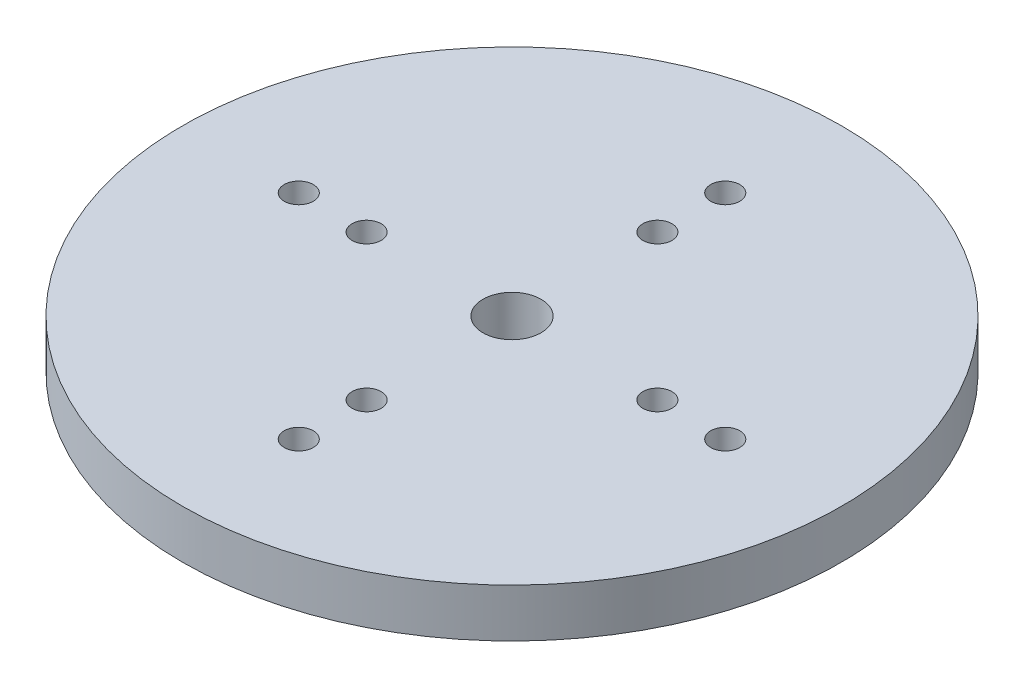
SolidWorks part; units mm, degrees
ref_plane "Front Plane" through (0, 0, 0) normal (0, 0, 1) x (1, 0, 0)
ref_plane "Top Plane" through (0, 0, 0) normal (0, 1, 0) x (1, 0, 0)
ref_plane "Right Plane" through (0, 0, 0) normal (1, 0, 0) x (0, 0, -1)
sketch "Sketch2" plane through (0, 0, 0) normal (0, 1, 0) x (1, 0, 0)
  circle A0 centre (0, 0) radius 34
  dimension "D1" = 68
extrude "Boss-Extrude1" add sketch "Sketch2" along normal blind 5
sketch "Sketch3" plane through (0, 0, 0) normal (0, -1, 0) x (1, 0, 0)
  circle A0 centre (0, 0) radius 22
  circle A1 centre (0, 22) radius 1.5
  circle A2 centre (0, 0) radius 22
  circle A3 centre (22, 0) radius 1.5
  circle A4 centre (0, 0) radius 22
  circle A5 centre (0, -22) radius 1.5
  circle A6 centre (0, 0) radius 22
  circle A7 centre (-22, 0) radius 1.5
  point P3 (0, 22)
  point P5 (22, 0)
  point P7 (0, -22)
  point P9 (-22, 0)
  point P29 (0, 0)
  dimension "D1" = 44
  dimension "D2" = 3
  dimension "D3" = 4
extrude "Cut-Extrude1" cut sketch "Sketch3" against normal blind 5 contours A1 | A7 | A5 | A3
sketch "Sketch5" plane through (0, 0, 0) normal (0, -1, 0) x (1, 0, 0)
  circle A0 centre (0, 0) radius 15
  circle A1 centre (0, 15) radius 1.5
  circle A2 centre (15, 0) radius 1.5
  circle A3 centre (0, -15) radius 1.5
  circle A4 centre (-15, 0) radius 1.5
  point P14 (0, 0)
  dimension "D1" = 30
  dimension "D2" = 3
  dimension "D3" = 4
extrude "Cut-Extrude2" cut sketch "Sketch5" against normal blind 5 contours A3 | A2 | A1 | A4
sketch "Sketch6" plane through (0, 0, 0) normal (0, -1, 0) x (1, 0, 0)
  circle A0 centre (0, 0) radius 10
  dimension "D1" = 20
extrude "Boss-Extrude2" add sketch "Sketch6" along normal blind 5
sketch "Sketch7" plane through (0, -5, 0) normal (0, -1, 0) x (-1, 0, 0)
  line L0 (0, 0) -> (0, -12.0475) construction
  line L1 (0, 0) -> (-18.343, 0) construction
  circle A0 centre (5.5, -3.985) radius 2
  circle A2 centre (-5.5, -3.985) radius 2
  circle A3 centre (-5.5, 3.985) radius 2
  circle A4 centre (5.5, 3.985) radius 2
  dimension "D1" = 4
  dimension "D2" = 7.97
  dimension "D3" = 11
extrude "Cut-Extrude3" cut sketch "Sketch7" against normal blind 5
sketch "Sketch8" plane through (0, -5, 0) normal (0, -1, 0) x (1, 0, 0)
  circle A0 centre (0, 0) radius 3
  dimension "D1" = 6
extrude "Cut-Extrude4" cut sketch "Sketch8" against normal blind 10
hole_wizard "Ø3.0 (3) Diameter Hole1" positions "3DSketch6" profile "Sketch14" hole size "Ø3.0" standard "ISO"
sketch3d "3DSketch6"
  line L0 (0, 0, 0) -> (0, -8.7526, 0) construction
  point P0 (0.0268, -2.5, -10)
  dimension "D1" = 2.5
sketch "Sketch14" plane through (0.0268, -2.5, -10) normal (0, 1, 0) x (-1, 0, -0.0027)
  line L0 (0, 0) -> (0, 8.7413)
  line L1 (0, 8.7413) -> (1.5, 7.84)
  line L2 (1.5, 7.84) -> (1.5, 0)
  line L5 (1.5, 0) -> (0, 0)
  line L10 (0, 8.7413) -> (-1.5, 7.84) construction
  line L11 (0, -6.35) -> (0, 107.95) construction
  dimension "Hole Dia." = 3
  dimension "Hole Depth" = 7.84
  dimension "Drill Angle" = 118
